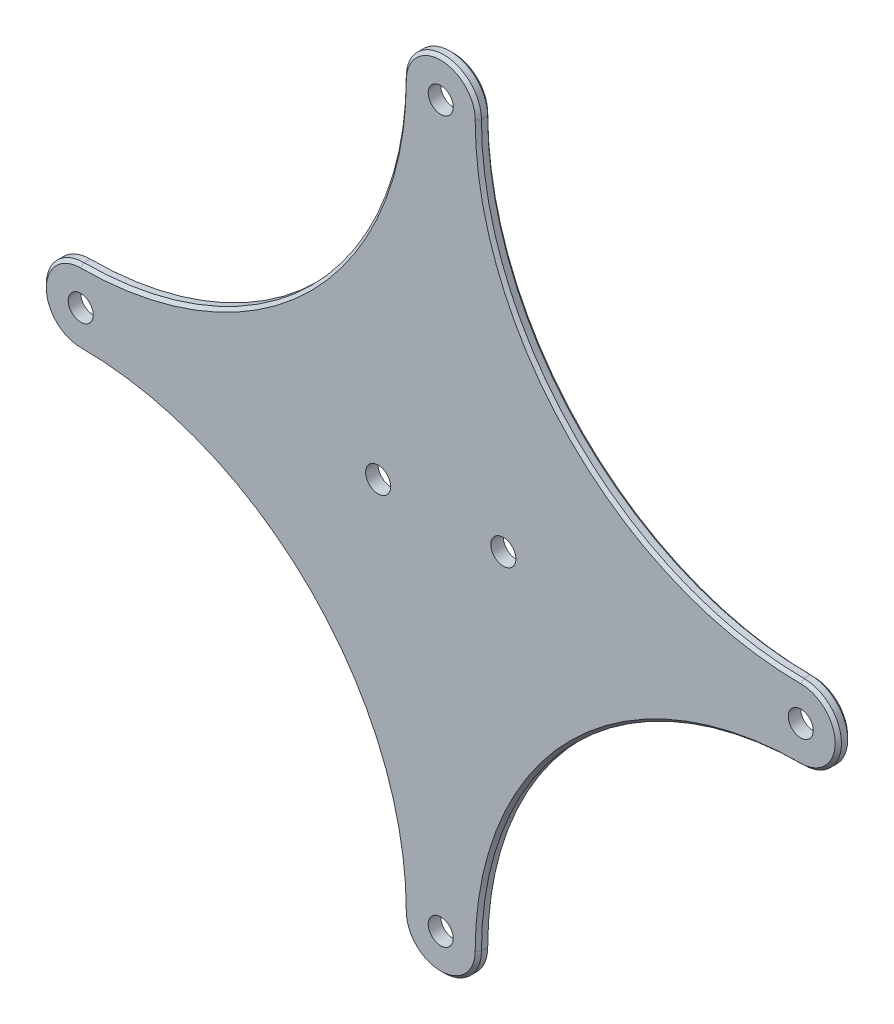
SolidWorks part; units mm, degrees
material "7075-T6 (SN)"
ref_plane "Ön Düzlem" through (0, 0, 0) normal (0, 0, 1) x (1, 0, 0)
ref_plane "Üst Düzlem" through (0, 0, 0) normal (0, 1, 0) x (1, 0, 0)
ref_plane "Sağ Düzlem" through (0, 0, 0) normal (1, 0, 0) x (0, 0, -1)
sketch "Çizim1" plane through (0, 0, 0) normal (0, 0, 1) x (1, 0, 0)
  line L0 (0, 0) -> (0, 115) construction
  line L1 (20, 0) -> (-20, 0) construction
  circle A0 centre (0, 0) radius 132.5
  circle A1 centre (0, 115) radius 4
  circle A2 centre (115, 0) radius 4
  circle A3 centre (0, -115) radius 4
  circle A4 centre (-115, 0) radius 4
  circle A5 centre (0, 115) radius 13 construction
  circle A6 centre (-20, 0) radius 4
  circle A7 centre (20, 0) radius 4
  point P15 (0, 0)
  dimension "D1" = 265
  dimension "D2" = 8
  dimension "D5" = 26
  dimension "D7" = 8
  dimension "D8" = 8
  dimension "D3" = 115
  dimension "D6" = 40
  dimension "D4" = 4
extrude "Yükseklik-Ekstrüzyon1" add sketch "Çizim1" along normal blind 4
sketch "Sketch1" plane through (0, 0, 4) normal (0, 0, 1) x (1, 0, 0)
  line L1 (0, 115) -> (0, 0) construction
  line L2 (0, 0) -> (115, 0) construction
  arc A0 (12, 115) -> (-12, 115) centre (0, 115) ccw
  arc A1 (-115, 12) -> (-115, -12) centre (-115, 0) ccw
  arc A2 (-115, 12) -> (-12, 115) centre (-115, 115) ccw
  arc A3 (115, 12) -> (12, 115) centre (115, 115) cw
  arc A4 (115, -12) -> (115, 12) centre (115, 0) ccw
  arc A5 (12, -115) -> (-12, -115) centre (0, -115) cw
  arc A6 (115, -12) -> (12, -115) centre (115, -115) ccw
  arc A7 (-115, -12) -> (-12, -115) centre (-115, -115) cw
  circle A8 centre (0, 0) radius 147.8965
  dimension "D1" = 24
  dimension "D2" = 24
  dimension "D3" = 24
extrude "Cut-Extrude2" cut sketch "Sketch1" against normal blind 10 contours A5 A7 A1 A2 A0 A3 A4 A6 | A8
chamfer "Chamfer1" distance 1 angle 45 16 edges at (42.168, 42.168, 0) (0, 127, 0) (127, 0, 0) (-42.168, 42.168, 0) (42.168, -42.168, 0) (-127, 0, 0) (0, -127, 0) (-42.168, -42.168, 0) (-42.168, 42.168, 4) (0, 127, 4) (-127, 0, 4) (42.168, 42.168, 4) (-42.168, -42.168, 4) (127, 0, 4) (0, -127, 4) (42.168, -42.168, 4)
